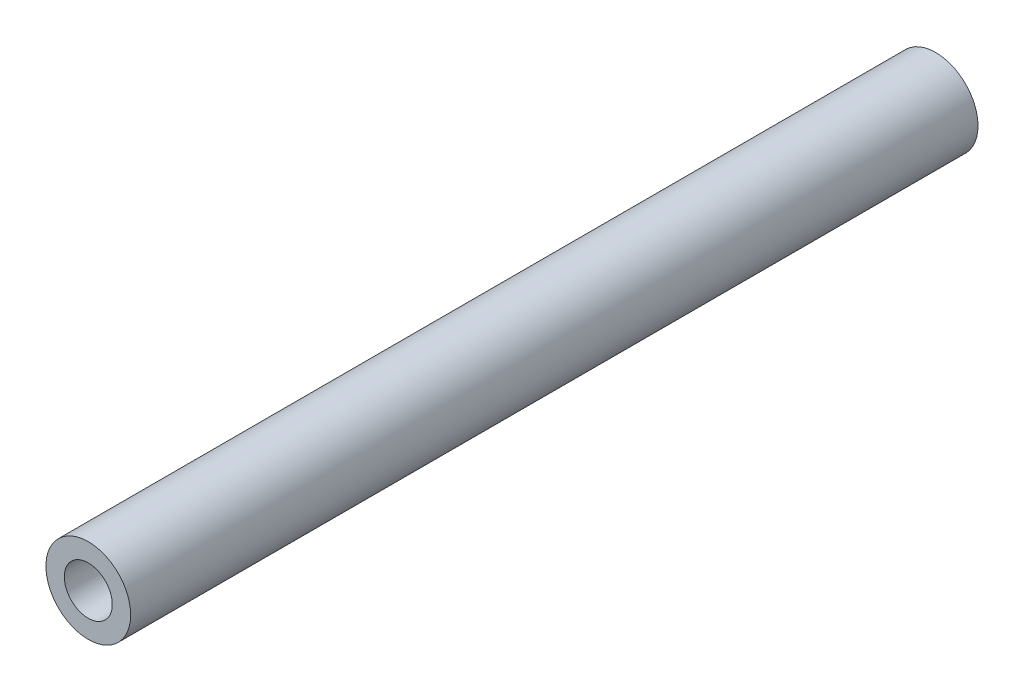
SolidWorks part; units mm, degrees
ref_plane "正面" through (0, 0, 0) normal (0, 0, 1) x (1, 0, 0)
ref_plane "平面" through (0, 0, 0) normal (0, 1, 0) x (1, 0, 0)
ref_plane "右側面" through (0, 0, 0) normal (1, 0, 0) x (0, 0, -1)
sketch "ｽｹｯﾁ1" plane through (0, 0, 0) normal (0, 0, 1) x (1, 0, 0)
  circle A0 centre (0, 0) radius 3
  dimension "D1" = 6
extrude "ﾎﾞｽ - 押し出し1" add sketch "ｽｹｯﾁ1" along normal blind 60
hole_wizard "M3 すきま穴1" positions "ｽｹｯﾁ2" profile "ｽｹｯﾁ3" hole size "M3" standard "JIS" end condition through all
sketch "ｽｹｯﾁ2" plane through (0, 0, 0) normal (0, 0, -1) x (-1, 0, 0)
  point P0 (0, 0)
sketch "ｽｹｯﾁ3" plane through (0, 0, 0) normal (1, 0, 0) x (0, 1, 0)
  line L0 (0, 0) -> (0, 60)
  line L1 (0, 60) -> (1.7, 60)
  line L2 (1.7, 60) -> (1.7, 0)
  line L5 (1.7, 0) -> (0, 0)
  line L11 (0, -6.35) -> (0, 107.95) construction
  dimension "通し穴の直径" = 3.4
  dimension "通し穴の深さ" = 60
